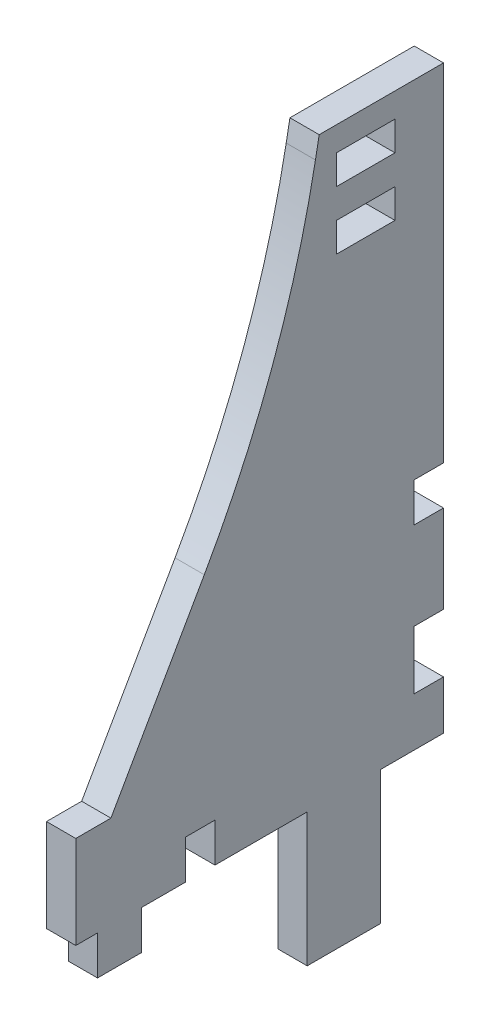
SolidWorks part; units mm, degrees
ref_plane "Front Plane" through (0, 0, 0) normal (0, 0, 1) x (1, 0, 0)
ref_plane "Top Plane" through (0, 0, 0) normal (0, 1, 0) x (1, 0, 0)
ref_plane "Right Plane" through (0, 0, 0) normal (1, 0, 0) x (0, 0, -1)
sketch "Sketch1" plane through (0, 0, 0) normal (1, 0, 0) x (0, 0, -1)
  line L0 (86.3215, 73.4228) -> (60.8261, 73.4228)
  line L1 (60.8261, 73.4228) -> (60.0603, 69.3161)
  line L2 (18.1126, -26.6059) -> (10.9033, -26.6059)
  line L3 (10.9033, -26.6059) -> (10.9033, -45.6224)
  line L4 (10.9033, -45.6224) -> (15.3675, -45.6224)
  line L5 (15.3675, -45.6224) -> (15.3675, -53.6263)
  line L6 (15.3675, -53.6263) -> (24.3675, -53.6263)
  line L7 (24.3675, -53.6263) -> (24.3675, -45.6224)
  line L8 (24.3675, -45.6224) -> (33.4533, -45.6224)
  line L9 (58.3675, -45.6224) -> (58.3675, -72.9735)
  line L10 (58.3675, -72.9735) -> (73.3675, -72.9735)
  line L11 (73.3675, -72.9735) -> (73.3675, -45.6224)
  line L12 (73.3675, -45.6224) -> (86.3215, -45.6224)
  line L13 (86.3215, -45.6224) -> (86.3215, -35.6224)
  line L14 (86.3215, 2.3776) -> (86.3215, 73.4228)
  line L15 (80.3215, 2.3776) -> (86.3215, 2.3776)
  line L16 (80.3215, 2.3776) -> (80.3215, -5.6224)
  line L17 (80.3215, -5.6224) -> (86.3215, -5.6224)
  line L18 (86.3215, -23.6224) -> (86.3215, -5.6224)
  line L19 (80.3215, -23.6224) -> (86.3215, -23.6224)
  line L20 (80.3215, -23.6224) -> (80.3215, -35.6224)
  line L21 (80.3215, -35.6224) -> (86.3215, -35.6224)
  line L22 (64.3748, 73.4228) -> (64.3748, 68.4228) construction
  line L23 (37.2658, 7.0444) -> (18.1126, -26.6059)
  line L24 (76.6873, -45.6224) -> (76.6873, 73.4228) construction
  line L25 (64.3748, 68.4228) -> (76.3748, 68.4228)
  line L26 (64.3748, 68.4228) -> (64.3748, 62.4228)
  line L27 (64.3748, 62.4228) -> (76.3748, 62.4228)
  line L28 (76.3748, 68.4228) -> (76.3748, 62.4228)
  line L29 (64.3748, 56.4228) -> (76.3748, 56.4228)
  line L30 (64.3748, 56.4228) -> (64.3748, 50.4228)
  line L31 (64.3748, 50.4228) -> (76.3748, 50.4228)
  line L32 (76.3748, 56.4228) -> (76.3748, 50.4228)
  line L33 (64.3748, 62.4228) -> (64.3748, 56.4228) construction
  line L34 (76.3748, 62.4228) -> (86.3215, 62.4228) construction
  line L35 (33.4533, -45.6224) -> (33.4533, -37.6224)
  line L36 (33.4533, -37.6224) -> (39.4533, -37.6224)
  line L37 (39.4533, -37.6224) -> (39.4533, -45.6224)
  line L38 (33.4533, -43.216) -> (24.3675, -43.216) construction
  line L39 (39.4533, -45.6224) -> (58.3675, -45.6224)
  arc A0 (60.0603, 69.3161) -> (37.2658, 7.0444) centre (-136.5508, 105.9778) cw
  dimension "D1" = 200
extrude "Boss-Extrude1" add sketch "Sketch1" along normal blind 6
